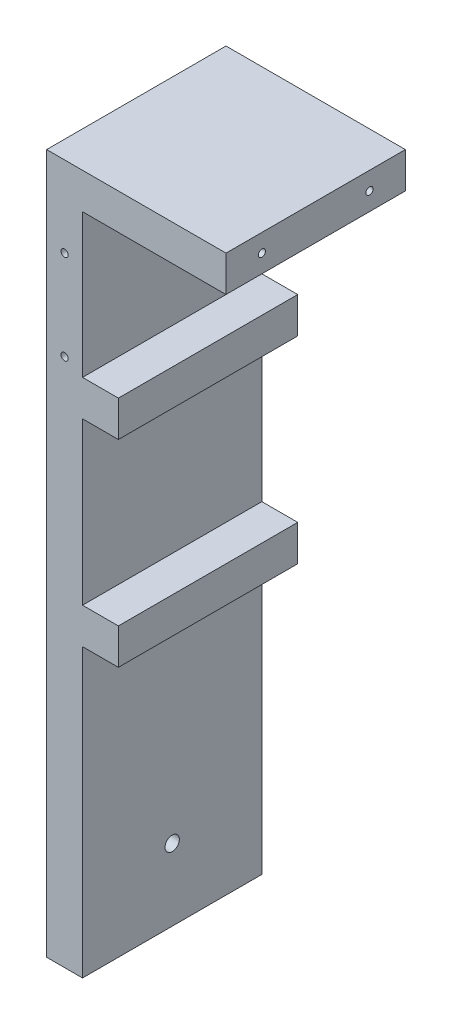
SolidWorks part; units mm, degrees
material "Buche"
ref_plane "Ebene vorne" through (0, 0, 0) normal (0, 0, 1) x (1, 0, 0)
ref_plane "Ebene oben" through (0, 0, 0) normal (0, 1, 0) x (1, 0, 0)
ref_plane "Ebene rechts" through (0, 0, 0) normal (1, 0, 0) x (0, 0, -1)
sketch "Skizze1" plane through (0, 0, 0) normal (1, 0, 0) x (0, 0, -1)
  line L1 (-25, 92.5) -> (25, 92.5)
  line L2 (-25, 92.5) -> (-25, -92.5)
  line L3 (-25, -92.5) -> (25, -92.5)
  line L4 (25, 92.5) -> (25, -92.5)
  line L5 (-25, 92.5) -> (25, -92.5) construction
  line L6 (-25, -92.5) -> (25, 92.5) construction
  point P0 (0, 0)
  dimension "D1" = 185
  dimension "D2" = 50
extrude "Aufsatz-Linear austragen1" add sketch "Skizze1" along normal blind 10
sketch "Skizze3" plane through (0, 0, 25) normal (0, 0, 1) x (1, 0, 0)
  line L0 (10, 92.5) -> (10, -92.5) construction
  line L1 (10, 52.5) -> (20, 52.5)
  line L2 (10, 52.5) -> (10, 42.5)
  line L3 (10, 42.5) -> (20, 42.5)
  line L4 (20, 52.5) -> (20, 42.5)
  line L5 (10, 52.5) -> (20, 42.5) construction
  line L6 (10, 42.5) -> (20, 52.5) construction
  line L7 (10, 92.5) -> (0, 92.5) construction
  line L8 (10, -2.5) -> (20, -2.5)
  line L9 (10, -2.5) -> (10, -12.5)
  line L10 (10, -12.5) -> (20, -12.5)
  line L11 (20, -2.5) -> (20, -12.5)
  line L12 (10, -2.5) -> (20, -12.5) construction
  line L13 (10, -12.5) -> (20, -2.5) construction
  point P4 (15, 47.5)
  point P11 (15, -7.5)
  dimension "D1" = 10
  dimension "D2" = 50
  dimension "D3" = 45
extrude "Aufsatz-Linear austragen3" add sketch "Skizze3" against normal up to surface (50 mm away) up to face at (5, 0, -25)
sketch "Skizze4" plane through (10, 0, 0) normal (1, 0, 0) x (0, 0, -1)
  line L0 (0, 0) -> (0, -92.5) construction
  line L1 (-25, -92.5) -> (25, -92.5) construction
  circle A0 centre (0, -72.5) radius 2
  dimension "D1" = 4
  dimension "D2" = 20
extrude "Schnitt-Linear austragen1" cut sketch "Skizze4" against normal through all
sketch "Skizze6" plane through (0, 92.5, 0) normal (0, 1, 0) x (1, 0, 0)
  line L0 (10, 25) -> (0, 25) construction
  line L1 (0, -25) -> (50, -25)
  line L2 (0, -25) -> (0, 25)
  line L3 (0, 25) -> (50, 25)
  line L4 (50, -25) -> (50, 25)
  line L5 (0, -25) -> (50, 25) construction
  line L6 (0, 25) -> (50, -25) construction
  point P4 (25, 0)
  dimension "D1" = 50
extrude "Aufsatz-Linear austragen4" add sketch "Skizze6" along normal blind 10
sketch "Skizze7" plane through (0, 0, 25) normal (0, 0, 1) x (1, 0, 0)
  line L0 (0, 102.5) -> (50, 102.5) construction
  line L1 (25, 102.5) -> (50, 102.5) construction
  line L2 (25, 102.5) -> (25, 92.5) construction
  line L3 (25, 92.5) -> (50, 92.5) construction
  line L4 (50, 102.5) -> (50, 92.5) construction
  line L5 (25, 102.5) -> (50, 92.5) construction
  line L6 (25, 92.5) -> (50, 102.5) construction
  line L7 (0, 102.5) -> (0, -92.5) construction
  line L8 (25, 102.5) -> (0, 102.5) construction
  line L9 (25, 102.5) -> (25, 92.5) construction
  line L10 (25, 92.5) -> (0, 92.5) construction
  line L11 (0, 102.5) -> (0, 92.5) construction
  line L12 (25, 102.5) -> (0, 92.5) construction
  line L13 (25, 92.5) -> (0, 102.5) construction
  line L14 (10, 92.5) -> (10, 52.5) construction
  line L15 (0, 92.5) -> (10, 92.5) construction
  line L16 (0, 92.5) -> (0, 67.5) construction
  line L17 (0, 67.5) -> (10, 67.5) construction
  line L18 (10, 92.5) -> (10, 67.5) construction
  line L19 (0, 92.5) -> (10, 67.5) construction
  line L20 (0, 67.5) -> (10, 92.5) construction
  line L22 (10, 67.5) -> (0, 67.5) construction
  line L23 (10, 67.5) -> (10, 42.5) construction
  line L24 (10, 42.5) -> (0, 42.5) construction
  line L25 (0, 67.5) -> (0, 42.5) construction
  line L26 (10, 67.5) -> (0, 42.5) construction
  line L27 (10, 42.5) -> (0, 67.5) construction
  circle A0 centre (37.5, 97.5) radius 1 construction
  circle A1 centre (12.5, 97.5) radius 1 construction
  circle A2 centre (5, 80) radius 1
  circle A3 centre (5, 55) radius 1
  point P4 (37.5, 97.5)
  point P10 (12.5, 97.5)
  point P16 (5, 80)
  point P21 (5, 55)
  dimension "D2" = 2
  dimension "D1" = 50
extrude "Schnitt-Linear austragen2" cut sketch "Skizze7" against normal through all
sketch "Skizze8" plane through (50, 0, 0) normal (1, 0, 0) x (0, 0, -1)
  line L0 (-25, 102.5) -> (25, 102.5) construction
  line L1 (0, 102.5) -> (30, 102.5) construction
  line L2 (0, 102.5) -> (0, 92.5) construction
  line L3 (0, 92.5) -> (30, 92.5) construction
  line L4 (30, 102.5) -> (30, 92.5) construction
  line L5 (0, 102.5) -> (30, 92.5) construction
  line L6 (0, 92.5) -> (30, 102.5) construction
  line L7 (-25, 92.5) -> (25, 92.5) construction
  line L8 (0, 102.5) -> (-30, 102.5) construction
  line L9 (0, 102.5) -> (0, 92.5) construction
  line L10 (0, 92.5) -> (-30, 92.5) construction
  line L11 (-30, 102.5) -> (-30, 92.5) construction
  line L12 (0, 102.5) -> (-30, 92.5) construction
  line L13 (0, 92.5) -> (-30, 102.5) construction
  circle A0 centre (-15, 97.5) radius 1
  circle A1 centre (15, 97.5) radius 1
  point P4 (15, 97.5)
  point P9 (-15, 97.5)
  dimension "D2" = 2
  dimension "D1" = 30
extrude "Schnitt-Linear austragen3" cut sketch "Skizze8" against normal blind 10
